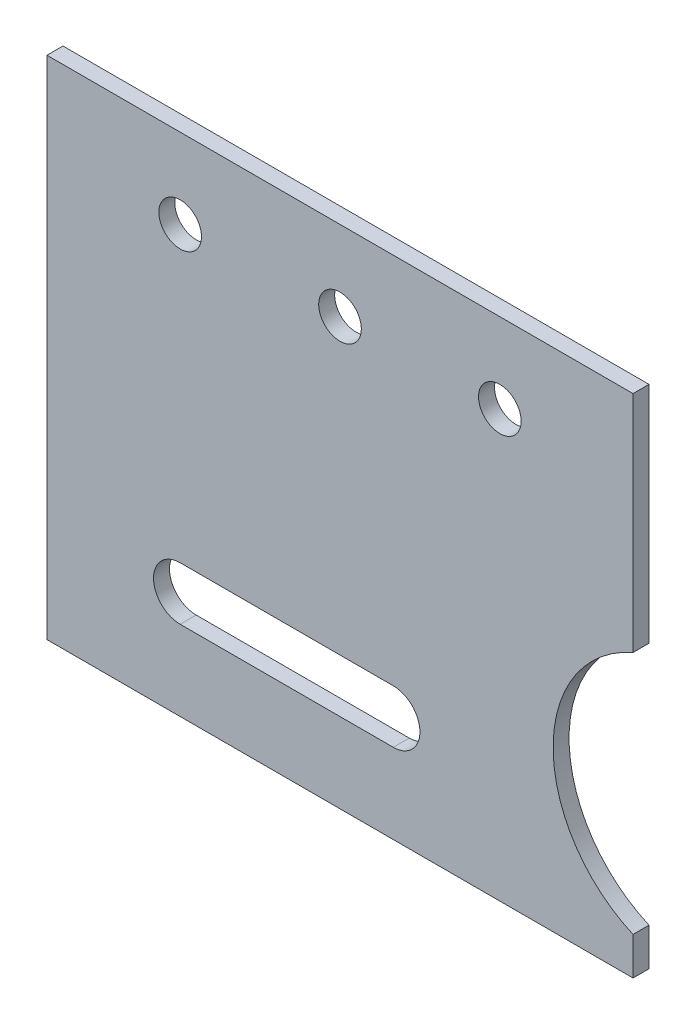
SolidWorks part; units mm, degrees
ref_plane "Ebene vorne" through (0, 0, 0) normal (0, 0, 1) x (1, 0, 0)
ref_plane "Ebene oben" through (0, 0, 0) normal (0, 1, 0) x (1, 0, 0)
ref_plane "Ebene rechts" through (0, 0, 0) normal (1, 0, 0) x (0, 0, -1)
sketch "Skizze1" plane through (0, 0, 0) normal (0, 0, 1) x (1, 0, 0)
  line L0 (25, 25) -> (65, 25)
  line L1 (0, 0) -> (110, 0)
  line L2 (0, 0) -> (0, 95)
  line L3 (0, 95) -> (110, 95)
  line L4 (110, 0) -> (110, 7.0871)
  line L5 (25, 15) -> (65, 15)
  line L6 (110, 52.9129) -> (110, 95)
  arc A0 (25, 25) -> (25, 15) centre (25, 20) ccw
  circle A3 centre (25, 80) radius 4
  circle A4 centre (55, 80) radius 4
  circle A5 centre (85, 80) radius 4
  arc A7 (65, 15) -> (65, 25) centre (65, 20) ccw
  arc A8 (110, 52.9129) -> (110, 7.0871) centre (120, 30) ccw
  dimension "D4" = 50
  dimension "D6" = 8
  dimension "D7" = 8
  dimension "D8" = 8
  dimension "D9" = 10
  dimension "D10" = 10
  dimension "D1" = 110
  dimension "D2" = 95
  dimension "D3" = 10
  dimension "D5" = 30
  dimension "D11" = 80
  dimension "D12" = 80
  dimension "D13" = 80
  dimension "D14" = 25
  dimension "D15" = 30
  dimension "D16" = 30
  dimension "D17" = 25
  dimension "D18" = 20
  dimension "D19" = 20
  dimension "D20" = 40
extrude "Aufsatz-Linear austragen1" add sketch "Skizze1" along normal blind 3
